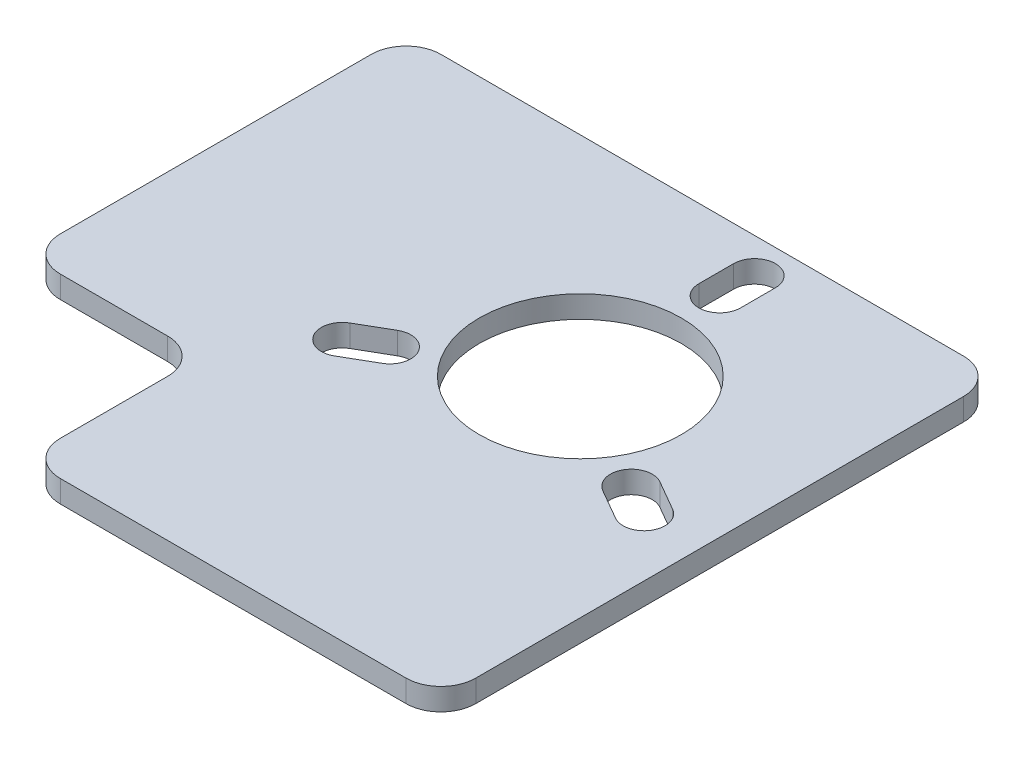
SolidWorks part; units mm, degrees
ref_plane "Front Plane" through (0, 0, 0) normal (0, 0, 1) x (1, 0, 0)
ref_plane "Top Plane" through (0, 0, 0) normal (0, 1, 0) x (1, 0, 0)
ref_plane "Right Plane" through (0, 0, 0) normal (1, 0, 0) x (0, 0, -1)
sketch "Sketch1" plane through (0, 0, 0) normal (0, 1, 0) x (1, 0, 0)
  line L1 (0, 0) -> (170, 0)
  line L2 (0, 0) -> (0, 160)
  line L3 (0, 160) -> (170, 160)
  line L4 (170, 0) -> (170, 160)
  circle A0 centre (110, 100) radius 29
  dimension "D3" = 58
  dimension "D4" = 60
  dimension "D5" = 60
  dimension "D1" = 170
  dimension "D2" = 160
extrude "Boss-Extrude1" add sketch "Sketch1" along normal blind 6.35
sketch "Sketch2" plane through (0, 6.35, 0) normal (0, 1, 0) x (1, 0, 0)
  line L1 (0, 0) -> (50.8, 0)
  line L2 (0, 0) -> (0, 50.8)
  line L3 (0, 50.8) -> (50.8, 50.8)
  line L4 (50.8, 0) -> (50.8, 50.8)
  dimension "D1" = 50.8
  dimension "D2" = 50.8
extrude "Cut-Extrude1" cut sketch "Sketch2" against normal through all
fillet "Fillet1" radius 10 6 edges at (170, 3.175, -160) (170, 3.175, 0) (0, 3.175, -160) (50.8, 3.175, -50.8) (50.8, 3.175, 0) (0, 3.175, -50.8)
sketch "Sketch3" plane through (0, 6.35, 0) normal (0, 1, 0) x (1, 0, 0)
  line L0 (110, 100) -> (66.6987, 75) construction
  line L1 (110, 100) -> (153.3013, 75) construction
  line L2 (110, 100) -> (110, 150) construction
  line L3 (110, 100) -> (139.8398, 100) construction
  line L4 (66.6987, 75) -> (75.359, 80) construction
  line L5 (63.6987, 80.1962) -> (72.359, 85.1962)
  line L6 (69.6987, 69.8038) -> (78.359, 74.8038)
  line L7 (153.3013, 75) -> (144.641, 80) construction
  line L8 (150.3013, 69.8038) -> (141.641, 74.8038)
  line L9 (156.3013, 80.1962) -> (147.641, 85.1962)
  line L10 (110, 150) -> (110, 140) construction
  line L11 (116, 150) -> (116, 140)
  line L12 (104, 150) -> (104, 140)
  arc A0 (63.6987, 80.1962) -> (69.6987, 69.8038) centre (66.6987, 75) ccw
  arc A1 (78.359, 74.8038) -> (72.359, 85.1962) centre (75.359, 80) ccw
  arc A2 (150.3013, 69.8038) -> (156.3013, 80.1962) centre (153.3013, 75) ccw
  arc A3 (147.641, 85.1962) -> (141.641, 74.8038) centre (144.641, 80) ccw
  arc A4 (116, 150) -> (104, 150) centre (110, 150) ccw
  arc A5 (104, 140) -> (116, 140) centre (110, 140) ccw
  point P3 (71.0289, 77.5)
  point P12 (148.9711, 77.5)
  point P18 (110, 145)
  dimension "D4" = 6
  dimension "D1" = 50
  dimension "D2" = 30
  dimension "D3" = 30
  dimension "D5" = 10
extrude "Cut-Extrude2" cut sketch "Sketch3" against normal through all
